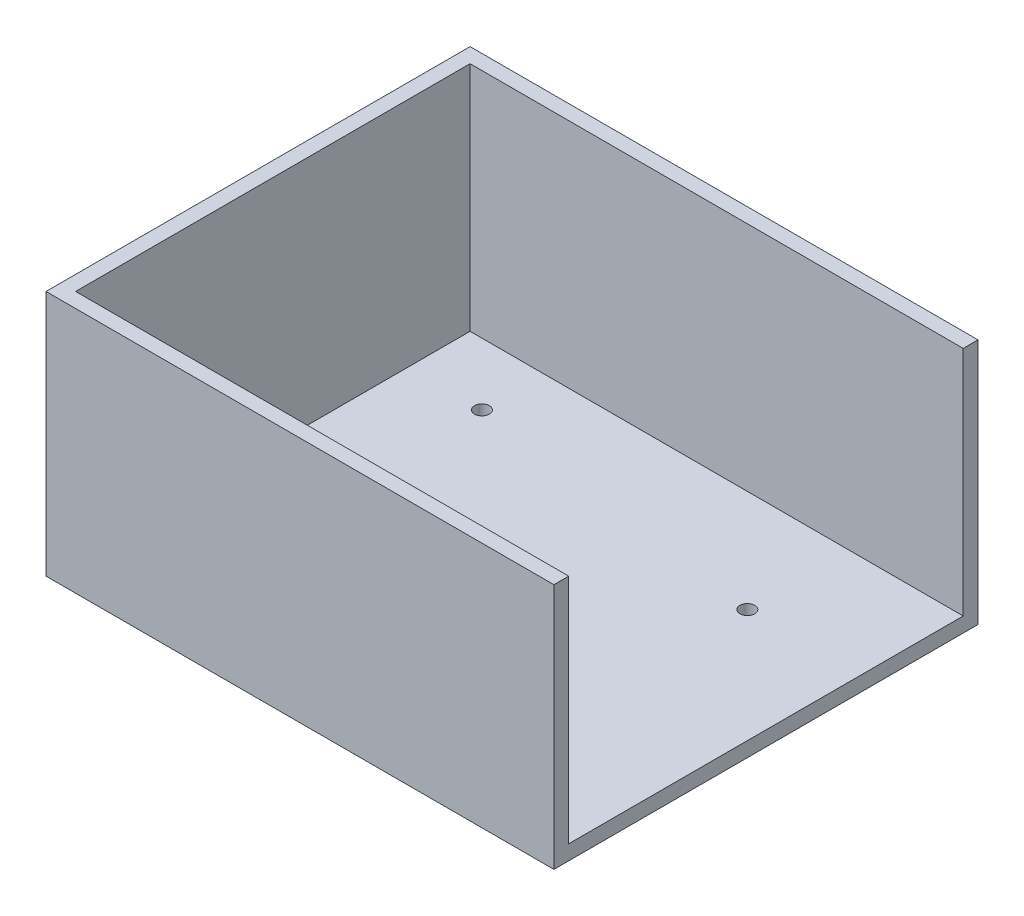
SolidWorks part; units mm, degrees
ref_plane "Piano frontale" through (0, 0, 0) normal (0, 0, 1) x (1, 0, 0)
ref_plane "Piano superiore" through (0, 0, 0) normal (0, 1, 0) x (1, 0, 0)
ref_plane "Piano destro" through (0, 0, 0) normal (1, 0, 0) x (0, 0, -1)
sketch "Schizzo1" plane through (0, 0, 0) normal (0, 1, 0) x (1, 0, 0)
  line L0 (0, 40) -> (100, 40) construction
  line L1 (0, 0) -> (100, 0)
  line L2 (0, 0) -> (0, 80)
  line L3 (0, 80) -> (100, 80)
  line L4 (100, 0) -> (100, 80)
  line L5 (50, 0) -> (50, 80) construction
  line L6 (0, 67.4) -> (100, 67.4) construction
  line L8 (0, 59.25) -> (100, 59.25) construction
  circle A0 centre (15, 67.4) radius 1.5
  circle A1 centre (15, 12.6) radius 1.5
  circle A2 centre (76.979, 59.25) radius 1.5
  circle A3 centre (76.979, 20.75) radius 1.5
  point P21 (76.979, 59.25)
  point P22 (13.5, 67.4)
  dimension "D5" = 3
  dimension "D6" = 15
  dimension "D10" = 3
  dimension "D1" = 100
  dimension "D2" = 80
  dimension "D4" = 27.4
  dimension "D7" = 19.25
  dimension "D9" = 64
extrude "Estrusione-Estrusione1" add sketch "Schizzo1" along normal blind 3
ref_plane "Piano1" through (0, 0, -40) normal (0, 0, 1) x (1, 0, 0)
sketch "Schizzo2" plane through (0, 0, 0) normal (0, 0, 1) x (1, 0, 0)
  line L0 (0, 0) -> (100, 0)
  line L1 (0, 0) -> (0, 50)
  line L2 (100, 0) -> (100, 50)
  line L3 (0, 50) -> (100, 50)
  dimension "D1" = 50
extrude "Estrusione-Estrusione2" add sketch "Schizzo2" along normal blind 3
mirror "Specchia1" about plane through (0, 0, -40) normal (0, 0, 1) of "Estrusione-Estrusione2"
ref_plane "Piano2" through (50, 0, 0) normal (1, 0, 0) x (0, 0, -1)
sketch "Schizzo3" plane through (0, 0, 0) normal (-1, 0, 0) x (0, 0, 1)
  line L0 (-83, 0) -> (3, 0)
  line L1 (-83, 0) -> (-83, 50)
  line L2 (3, 0) -> (3, 50)
  line L3 (-83, 50) -> (3, 50)
  line L4 (3, 50) -> (3, 0) construction
  point P0 (3, 50)
  dimension "D1" = 50
extrude "Estrusione-Estrusione3" add sketch "Schizzo3" along normal blind 3
sketch "Schizzo4" plane through (-3, 0, 0) normal (-1, 0, 0) x (0, 0, 1)
  circle A0 centre (-60.1826, 8.7629) radius 3.5
  point P2 (-59.0698, 12.8095)
  point P3 (0, 0)
  point P4 (0, 0)
  point P5 (-60.7896, 13.6188)
  point P6 (-60.1826, 8.7629)
  dimension "D1" = 7
